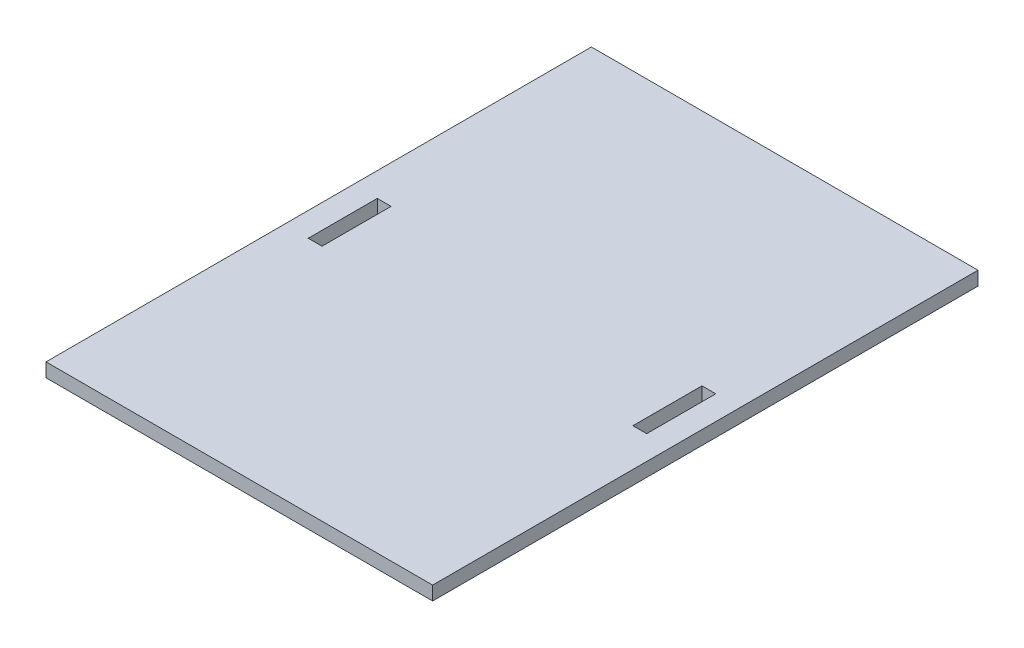
SolidWorks part; units mm, degrees
ref_plane "前视基准面" through (0, 0, 0) normal (0, 0, 1) x (1, 0, 0)
ref_plane "上视基准面" through (0, 0, 0) normal (0, 1, 0) x (1, 0, 0)
ref_plane "右视基准面" through (0, 0, 0) normal (1, 0, 0) x (0, 0, -1)
sketch "草图1" plane through (0, 0, 0) normal (0, 0, 1) x (1, 0, 0)
  line L0 (-51.8, 0) -> (51.8, 0) construction
  line L1 (0, 0) -> (28, -54.9531) construction
  line L2 (0, 0) -> (-28, -54.9531) construction
  line L3 (-28, -54.9531) -> (28, -54.9531)
  line L4 (-28, -52.9531) -> (-28, -54.9531)
  line L7 (-28, -52.9531) -> (28, -52.9531)
  line L8 (28, -54.9531) -> (28, -52.9531)
  dimension "D1" = 2
  dimension "D2" = 63
  dimension "D3" = 63
  dimension "D4" = 56
extrude "凸台-拉伸1" add sketch "草图1" along normal blind 79
sketch "草图3" plane through (0, -54.9531, 0) normal (0, -1, 0) x (1, 0, 0)
  line L0 (-28, 39.5) -> (28, 39.5) construction
  line L1 (-28, 79) -> (-28, 0) construction
  line L2 (28, 79) -> (28, 0) construction
  line L3 (0, 79) -> (0, 0) construction
  line L4 (-28, 79) -> (28, 79) construction
  line L5 (24.515, 44.5) -> (22.515, 34.5) construction
  line L6 (-24.515, 34.5) -> (-22.515, 34.5)
  line L7 (-24.515, 34.5) -> (-24.515, 44.5)
  line L8 (-24.515, 44.5) -> (-22.515, 44.5)
  line L9 (-22.515, 34.5) -> (-22.515, 44.5)
  line L10 (-24.515, 34.5) -> (-22.515, 44.5) construction
  line L11 (-24.515, 44.5) -> (-22.515, 34.5) construction
  line L12 (24.515, 34.5) -> (22.515, 44.5) construction
  line L13 (22.515, 34.5) -> (22.515, 44.5)
  line L14 (24.515, 44.5) -> (22.515, 44.5)
  line L15 (24.515, 34.5) -> (24.515, 44.5)
  line L16 (24.515, 34.5) -> (22.515, 34.5)
  point P11 (-23.515, 39.5)
  point P20 (23.515, 39.5)
  dimension "D1" = 2
  dimension "D2" = 10
  dimension "D3" = 47.03
extrude "切除-拉伸1" cut sketch "草图3" against normal blind 79
